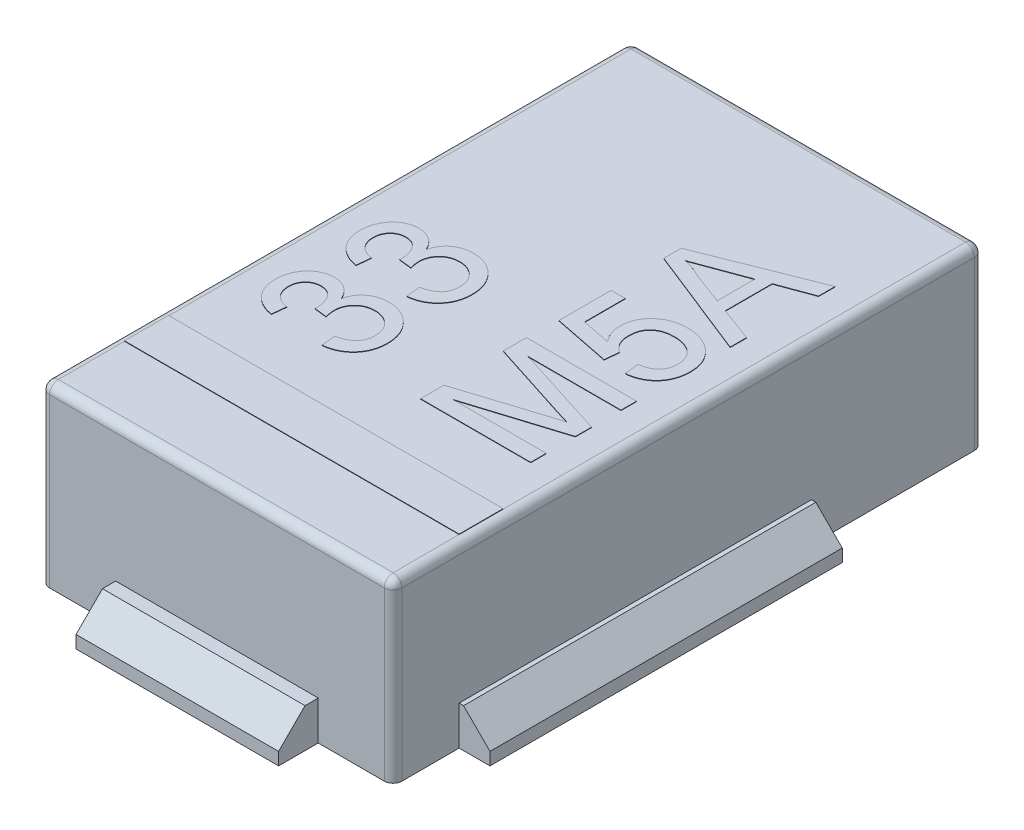
SolidWorks part; units mm, degrees
ref_plane "Front Plane" through (0, 0, 0) normal (0, 0, 1) x (1, 0, 0)
ref_plane "Top Plane" through (0, 0, 0) normal (0, 1, 0) x (1, 0, 0)
ref_plane "Right Plane" through (0, 0, 0) normal (1, 0, 0) x (0, 0, -1)
sketch "Sketch1" plane through (0, 0, 0) normal (0, 1, 0) x (1, 0, 0)
  line L1 (-1.016, 1.7018) -> (1.016, 1.7018)
  line L2 (-1.016, 1.7018) -> (-1.016, -1.7018)
  line L3 (-1.016, -1.7018) -> (1.016, -1.7018)
  line L4 (1.016, 1.7018) -> (1.016, -1.7018)
  point P4 (1.016, 0)
  point P6 (0, 1.7018)
  dimension "D1" = 2.032
  dimension "D2" = 3.4036
extrude "Boss-Extrude1" add sketch "Sketch1" along normal blind 1.016
sketch "Sketch2" plane through (0, 0, 0) normal (0, -1, 0) x (1, 0, 0)
  line L0 (-1.016, 1.7018) -> (1.016, 1.7018) construction
  line L1 (0.5842, 1.397) -> (-0.5842, 1.397)
  line L2 (0.5842, 1.397) -> (0.5842, 1.9304)
  line L3 (0.5842, 1.9304) -> (-0.5842, 1.9304)
  line L4 (-0.5842, 1.397) -> (-0.5842, 1.9304)
  line L5 (0.4064, -1.397) -> (-0.4064, -1.397)
  line L6 (0.4064, -1.397) -> (0.4064, -1.9304)
  line L7 (0.4064, -1.9304) -> (-0.4064, -1.9304)
  line L8 (-0.4064, -1.397) -> (-0.4064, -1.9304)
  point P8 (0, 1.397)
  point P10 (0, -1.397)
  dimension "D1" = 0.8128
  dimension "D2" = 1.1684
  dimension "D3" = 0.3048
  dimension "D4" = 0.5334
  dimension "D5" = 3.8608
extrude "Boss-Extrude2" add sketch "Sketch2" against normal blind 0.225
sketch "Sketch3" plane through (1.016, 0, 0) normal (1, 0, 0) x (0, 0, -1)
  line L0 (-1.7018, 0) -> (1.7018, 0) construction
  line L1 (-1.3208, 0) -> (0.7112, 0)
  line L2 (-1.3208, 0) -> (-1.3208, 0.225)
  line L3 (-1.3208, 0.225) -> (0.7112, 0.225)
  line L4 (0.7112, 0) -> (0.7112, 0.225)
  line L5 (1.9304, 0.225) -> (1.9304, 0) construction
  line L6 (-1.7018, 1.016) -> (-1.7018, 0) construction
  dimension "D1" = 2.032
  dimension "D2" = 0.381
extrude "Boss-Extrude3" add sketch "Sketch3" along normal blind 0.1778
fillet "Fillet1" radius 0.0508 8 edges at (0, 1.016, -1.7018) (1.016, 1.016, 0) (0, 1.016, 1.7018) (-1.016, 1.016, 0) (-1.016, 0.508, 1.7018) (1.016, 0.508, 1.7018) (-1.016, 0.508, -1.7018) (1.016, 0.508, -1.7018)
chamfer "Chamfer1" distance 0.1524 angle 45 3 edges at (0, 0.225, -1.9304) (1.1938, 0.225, 0.3048) (0, 0.225, 1.9304)
sketch "Sketch4" plane through (0, 1.016, 0) normal (0, 1, 0) x (1, 0, 0)
  line L0 (0.9652, -1.651) -> (0.9652, 1.651) construction
  line L1 (0.9652, -1.27) -> (-0.9652, -1.27)
  line L2 (0.9652, -1.27) -> (0.9652, -1.016)
  line L3 (0.9652, -1.016) -> (-0.9652, -1.016)
  line L4 (-0.9652, -1.27) -> (-0.9652, -1.016)
  line L5 (-0.9652, 1.651) -> (-0.9652, -1.651) construction
  line L6 (-0.9652, -1.651) -> (0.9652, -1.651) construction
  line L7 (-0.2032, 1.651) -> (-0.2032, -0.762) construction
  line L8 (0.8128, 1.651) -> (0.8128, -0.762) construction
  line L9 (0.9652, 1.651) -> (-0.9652, 1.651) construction
  text T0 "33" font "Arial" height 0.635
  text T1 "M5A" font "Arial" height 0.635
  point P14 (0.3176, 2.463)
  point P15 (0.5343, -0.4897)
  point P16 (0, 0)
  point P17 (0.8128, 2.613)
  point P20 (0, 0)
  dimension "D1" = 0.254
  dimension "D2" = 0.381
  dimension "D3" = 0.889
  dimension "D4" = 0.762
  dimension "D5" = 1.016
extrude "Boss-Extrude4" add sketch "Sketch4" along normal blind 0.0025
